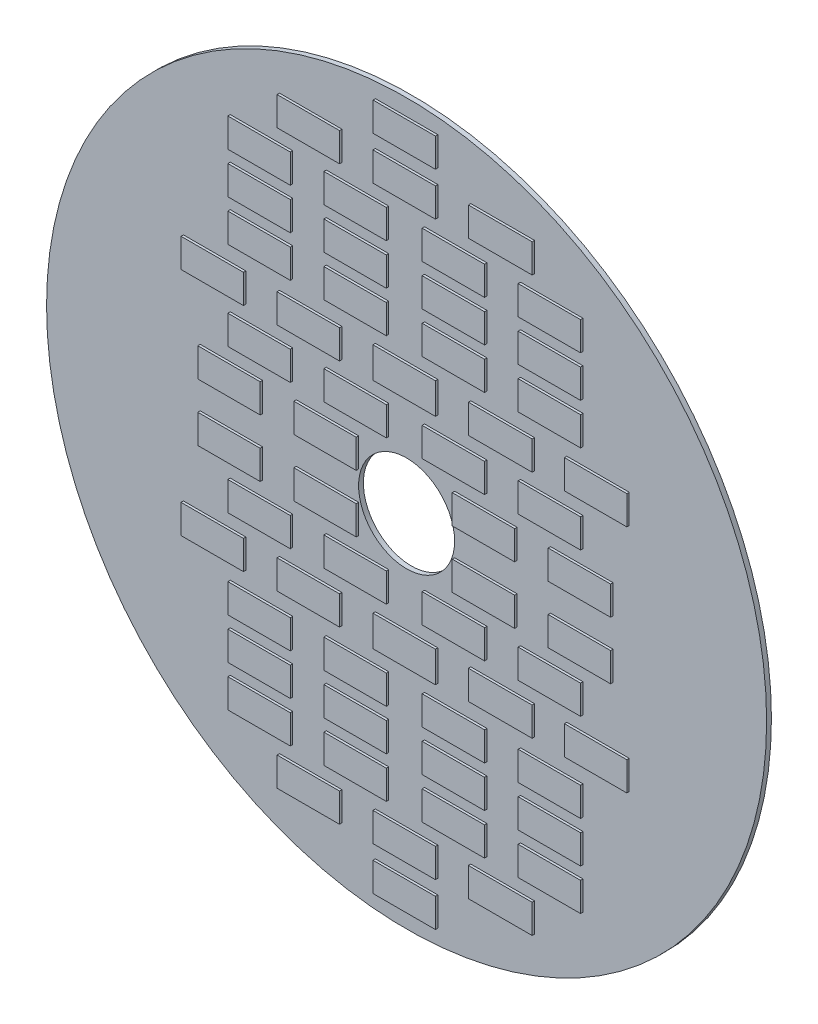
SolidWorks part; units mm, degrees
ref_plane "前视基准面" through (0, 0, 0) normal (0, 0, 1) x (1, 0, 0)
ref_plane "上视基准面" through (0, 0, 0) normal (0, 1, 0) x (1, 0, 0)
ref_plane "右视基准面" through (0, 0, 0) normal (1, 0, 0) x (0, 0, -1)
other "Configuration Table"
sketch "草图1" plane through (0, 0, 0) normal (0, 0, 1) x (1, 0, 0)
  line L5 (100, 90) -> (230, 90)
  line L6 (100, 90) -> (100, 30)
  line L8 (100, 30) -> (230, 30)
  line L12 (230, 90) -> (230, 30)
  line L14 (100, 90) -> (230, 30) construction
  line L18 (100, 30) -> (230, 90) construction
  line L24 (-1658.199, 0) -> (1658.199, 0) construction
  line L26 (0, 1113.9389) -> (0, -1113.9389) construction
  line L50 (300, 90) -> (430, 90)
  line L53 (300, 90) -> (300, 30)
  line L57 (300, 30) -> (430, 30)
  line L58 (430, 90) -> (430, 30)
  line L59 (300, 90) -> (430, 30) construction
  line L60 (300, 30) -> (430, 90) construction
  line L61 (37.3566, 180) -> (37.3566, 120)
  line L62 (237.3566, 120) -> (367.3566, 120)
  line L63 (237.3566, 180) -> (367.3566, 120) construction
  line L64 (37.3566, 120) -> (167.3566, 180) construction
  line L65 (237.3566, 180) -> (237.3566, 120)
  line L66 (367.3566, 180) -> (367.3566, 120)
  line L67 (37.3566, 180) -> (167.3566, 180)
  line L68 (37.3566, 180) -> (167.3566, 120) construction
  line L69 (237.3566, 180) -> (367.3566, 180)
  line L70 (237.3566, 120) -> (367.3566, 180) construction
  line L71 (37.3566, 120) -> (167.3566, 120)
  line L72 (167.3566, 180) -> (167.3566, 120)
  line L83 (37.3566, 364.2375) -> (37.3566, 304.2375)
  line L84 (237.3566, 304.2375) -> (367.3566, 304.2375)
  line L91 (133.7252, 270) -> (133.7252, 210)
  line L92 (333.7252, 210) -> (463.7252, 210)
  line L93 (333.7252, 270) -> (463.7252, 210) construction
  line L94 (133.7252, 210) -> (266.6142, 270) construction
  line L95 (333.7252, 270) -> (333.7252, 210)
  line L96 (463.7252, 270) -> (463.7252, 210)
  line L97 (133.7252, 270) -> (266.6142, 270)
  line L98 (133.7252, 270) -> (266.6142, 210) construction
  line L99 (333.7252, 270) -> (463.7252, 270)
  line L100 (333.7252, 210) -> (463.7252, 270) construction
  line L101 (133.7252, 210) -> (266.6142, 210)
  line L102 (266.6142, 270) -> (266.6142, 210)
  line L103 (-65, 274.2375) -> (-65, 210)
  line L104 (-65, 274.2375) -> (65, 274.2375)
  line L105 (-65, 210) -> (65, 210)
  line L106 (65, 274.2375) -> (65, 210)
  line L107 (-65, 210) -> (65, 274.2375) construction
  line L108 (-65, 274.2375) -> (65, 210) construction
  line L109 (-264.8303, 270) -> (-264.8303, 210)
  line L110 (-264.8303, 270) -> (-134.8303, 270)
  line L111 (-264.8303, 210) -> (-134.8303, 210)
  line L112 (-134.8303, 270) -> (-134.8303, 210)
  line L113 (-264.8303, 210) -> (-134.8303, 270) construction
  line L114 (-264.8303, 270) -> (-134.8303, 210) construction
  line L115 (-464.8303, 270) -> (-464.8303, 210)
  line L116 (-464.8303, 270) -> (-334.8303, 270)
  line L117 (-464.8303, 210) -> (-334.8303, 210)
  line L118 (-334.8303, 270) -> (-334.8303, 210)
  line L119 (-464.8303, 210) -> (-334.8303, 270) construction
  line L120 (-464.8303, 270) -> (-334.8303, 210) construction
  line L122 (237.3566, 364.2375) -> (237.3566, 304.2375)
  line L123 (367.3566, 364.2375) -> (367.3566, 304.2375)
  line L125 (37.3566, 364.2375) -> (167.3566, 364.2375)
  line L127 (237.3566, 364.2375) -> (367.3566, 364.2375)
  line L128 (37.3566, 304.2375) -> (167.3566, 304.2375)
  line L129 (167.3566, 364.2375) -> (167.3566, 304.2375)
  line L139 (237.3566, 364.2375) -> (367.3566, 304.2375) construction
  line L140 (37.3566, 304.2375) -> (167.3566, 364.2375) construction
  line L141 (37.3566, 364.2375) -> (167.3566, 304.2375) construction
  line L142 (237.3566, 304.2375) -> (367.3566, 364.2375) construction
  line L143 (37.3566, 450) -> (37.3566, 390)
  line L144 (237.3566, 390) -> (367.3566, 390)
  line L145 (237.3566, 450) -> (237.3566, 390)
  line L146 (367.3566, 450) -> (367.3566, 390)
  line L147 (37.3566, 450) -> (167.3566, 450)
  line L148 (237.3566, 450) -> (367.3566, 450)
  line L149 (37.3566, 390) -> (167.3566, 390)
  line L150 (167.3566, 450) -> (167.3566, 390)
  line L151 (237.3566, 450) -> (367.3566, 390) construction
  line L152 (37.3566, 390) -> (167.3566, 450) construction
  line L153 (37.3566, 450) -> (167.3566, 390) construction
  line L154 (237.3566, 390) -> (367.3566, 450) construction
  line L155 (37.3566, 535.7625) -> (37.3566, 475.7625)
  line L156 (237.3566, 475.7625) -> (367.3566, 475.7625)
  line L157 (237.3566, 535.7625) -> (237.3566, 475.7625)
  line L158 (367.3566, 535.7625) -> (367.3566, 475.7625)
  line L159 (37.3566, 535.7625) -> (167.3566, 535.7625)
  line L160 (237.3566, 535.7625) -> (367.3566, 535.7625)
  line L161 (37.3566, 475.7625) -> (167.3566, 475.7625)
  line L162 (167.3566, 535.7625) -> (167.3566, 475.7625)
  line L163 (237.3566, 535.7625) -> (367.3566, 475.7625) construction
  line L164 (37.3566, 475.7625) -> (167.3566, 535.7625) construction
  line L165 (37.3566, 535.7625) -> (167.3566, 475.7625) construction
  line L166 (237.3566, 475.7625) -> (367.3566, 535.7625) construction
  line L167 (-264.8303, 565.7625) -> (-134.8303, 625.7625) construction
  line L168 (133.7252, 565.7625) -> (266.6142, 565.7625)
  line L169 (-65, 565.7625) -> (65, 625.7625) construction
  line L170 (-65, 625.7625) -> (-65, 565.7625)
  line L171 (-264.8303, 625.7625) -> (-264.8303, 565.7625)
  line L172 (-134.8303, 625.7625) -> (-134.8303, 565.7625)
  line L173 (133.7252, 625.7625) -> (266.6142, 625.7625)
  line L174 (133.7252, 625.7625) -> (266.6142, 565.7625) construction
  line L175 (65, 625.7625) -> (65, 565.7625)
  line L176 (-264.8303, 625.7625) -> (-134.8303, 565.7625) construction
  line L177 (133.7252, 625.7625) -> (133.7252, 565.7625)
  line L178 (-65, 625.7625) -> (65, 625.7625)
  line L179 (-65, 565.7625) -> (65, 565.7625)
  line L180 (-264.8303, 565.7625) -> (-134.8303, 565.7625)
  line L181 (133.7252, 565.7625) -> (266.6142, 625.7625) construction
  line L182 (266.6142, 625.7625) -> (266.6142, 565.7625)
  line L183 (-264.8303, 625.7625) -> (-134.8303, 625.7625)
  line L184 (-65, 625.7625) -> (65, 565.7625) construction
  line L185 (-300, 90) -> (-300, 30)
  line L186 (-300, 30) -> (-430, 30)
  line L187 (-430, 90) -> (-430, 30)
  line L188 (-300, 90) -> (-430, 90)
  line L189 (-100, 30) -> (-230, 30)
  line L190 (-230, 90) -> (-230, 30)
  line L191 (-100, 90) -> (-230, 90)
  line L192 (-100, 90) -> (-100, 30)
  line L193 (-37.3566, 180) -> (-167.3566, 180)
  line L194 (-167.3566, 180) -> (-167.3566, 120)
  line L195 (-37.3566, 120) -> (-167.3566, 120)
  line L196 (-37.3566, 180) -> (-37.3566, 120)
  line L197 (-237.3566, 180) -> (-237.3566, 120)
  line L198 (-237.3566, 180) -> (-367.3566, 180)
  line L199 (-367.3566, 180) -> (-367.3566, 120)
  line L200 (-237.3566, 120) -> (-367.3566, 120)
  line L201 (-237.3566, 475.7625) -> (-367.3566, 535.7625) construction
  line L202 (-37.3566, 535.7625) -> (-167.3566, 475.7625) construction
  line L203 (-37.3566, 475.7625) -> (-167.3566, 535.7625) construction
  line L204 (-237.3566, 535.7625) -> (-367.3566, 475.7625) construction
  line L205 (-237.3566, 390) -> (-367.3566, 450) construction
  line L206 (-37.3566, 450) -> (-167.3566, 390) construction
  line L207 (-37.3566, 390) -> (-167.3566, 450) construction
  line L208 (-237.3566, 450) -> (-367.3566, 390) construction
  line L209 (-237.3566, 304.2375) -> (-367.3566, 364.2375) construction
  line L210 (-37.3566, 364.2375) -> (-167.3566, 304.2375) construction
  line L211 (-37.3566, 304.2375) -> (-167.3566, 364.2375) construction
  line L212 (-237.3566, 364.2375) -> (-367.3566, 304.2375) construction
  line L213 (-167.3566, 535.7625) -> (-167.3566, 475.7625)
  line L214 (-37.3566, 475.7625) -> (-167.3566, 475.7625)
  line L215 (-237.3566, 535.7625) -> (-367.3566, 535.7625)
  line L216 (-37.3566, 535.7625) -> (-167.3566, 535.7625)
  line L217 (-367.3566, 535.7625) -> (-367.3566, 475.7625)
  line L218 (-237.3566, 535.7625) -> (-237.3566, 475.7625)
  line L219 (-237.3566, 475.7625) -> (-367.3566, 475.7625)
  line L220 (-37.3566, 535.7625) -> (-37.3566, 475.7625)
  line L221 (-167.3566, 450) -> (-167.3566, 390)
  line L222 (-37.3566, 390) -> (-167.3566, 390)
  line L223 (-237.3566, 450) -> (-367.3566, 450)
  line L224 (-37.3566, 450) -> (-167.3566, 450)
  line L225 (-367.3566, 450) -> (-367.3566, 390)
  line L226 (-237.3566, 450) -> (-237.3566, 390)
  line L227 (-237.3566, 390) -> (-367.3566, 390)
  line L228 (-37.3566, 450) -> (-37.3566, 390)
  line L229 (-167.3566, 364.2375) -> (-167.3566, 304.2375)
  line L230 (-37.3566, 304.2375) -> (-167.3566, 304.2375)
  line L231 (-237.3566, 364.2375) -> (-367.3566, 364.2375)
  line L232 (-37.3566, 364.2375) -> (-167.3566, 364.2375)
  line L233 (-367.3566, 364.2375) -> (-367.3566, 304.2375)
  line L234 (-237.3566, 364.2375) -> (-237.3566, 304.2375)
  line L235 (-237.3566, 304.2375) -> (-367.3566, 304.2375)
  line L236 (-37.3566, 364.2375) -> (-37.3566, 304.2375)
  line L237 (-237.3566, -364.2375) -> (-367.3566, -304.2375) construction
  line L238 (-37.3566, -304.2375) -> (-167.3566, -364.2375) construction
  line L239 (-37.3566, -364.2375) -> (-167.3566, -304.2375) construction
  line L240 (-237.3566, -304.2375) -> (-367.3566, -364.2375) construction
  line L241 (-237.3566, -450) -> (-367.3566, -390) construction
  line L242 (-37.3566, -390) -> (-167.3566, -450) construction
  line L243 (-37.3566, -450) -> (-167.3566, -390) construction
  line L244 (-237.3566, -390) -> (-367.3566, -450) construction
  line L245 (-237.3566, -535.7625) -> (-367.3566, -475.7625) construction
  line L246 (-37.3566, -475.7625) -> (-167.3566, -535.7625) construction
  line L247 (-37.3566, -535.7625) -> (-167.3566, -475.7625) construction
  line L248 (-237.3566, -475.7625) -> (-367.3566, -535.7625) construction
  line L249 (-65, -625.7625) -> (65, -565.7625) construction
  line L250 (133.7252, -565.7625) -> (266.6142, -625.7625) construction
  line L251 (-264.8303, -625.7625) -> (-134.8303, -565.7625) construction
  line L252 (133.7252, -625.7625) -> (266.6142, -565.7625) construction
  line L253 (-65, -565.7625) -> (65, -625.7625) construction
  line L254 (-264.8303, -565.7625) -> (-134.8303, -625.7625) construction
  line L255 (237.3566, -475.7625) -> (367.3566, -535.7625) construction
  line L256 (37.3566, -535.7625) -> (167.3566, -475.7625) construction
  line L257 (37.3566, -475.7625) -> (167.3566, -535.7625) construction
  line L258 (237.3566, -535.7625) -> (367.3566, -475.7625) construction
  line L259 (237.3566, -390) -> (367.3566, -450) construction
  line L260 (37.3566, -450) -> (167.3566, -390) construction
  line L261 (37.3566, -390) -> (167.3566, -450) construction
  line L262 (237.3566, -450) -> (367.3566, -390) construction
  line L263 (237.3566, -304.2375) -> (367.3566, -364.2375) construction
  line L264 (37.3566, -364.2375) -> (167.3566, -304.2375) construction
  line L265 (37.3566, -304.2375) -> (167.3566, -364.2375) construction
  line L266 (237.3566, -364.2375) -> (367.3566, -304.2375) construction
  line L267 (-464.8303, -270) -> (-334.8303, -210) construction
  line L268 (-464.8303, -210) -> (-334.8303, -270) construction
  line L269 (-264.8303, -270) -> (-134.8303, -210) construction
  line L270 (-264.8303, -210) -> (-134.8303, -270) construction
  line L271 (-65, -274.2375) -> (65, -210) construction
  line L272 (-65, -210) -> (65, -274.2375) construction
  line L273 (333.7252, -210) -> (463.7252, -270) construction
  line L274 (133.7252, -270) -> (266.6142, -210) construction
  line L275 (133.7252, -210) -> (266.6142, -270) construction
  line L276 (333.7252, -270) -> (463.7252, -210) construction
  line L277 (237.3566, -120) -> (367.3566, -180) construction
  line L278 (37.3566, -180) -> (167.3566, -120) construction
  line L279 (37.3566, -120) -> (167.3566, -180) construction
  line L280 (237.3566, -180) -> (367.3566, -120) construction
  line L281 (300, -30) -> (430, -90) construction
  line L282 (300, -90) -> (430, -30) construction
  line L283 (100, -30) -> (230, -90) construction
  line L284 (100, -90) -> (230, -30) construction
  line L285 (-37.3566, -364.2375) -> (-37.3566, -304.2375)
  line L286 (-237.3566, -304.2375) -> (-367.3566, -304.2375)
  line L287 (-237.3566, -364.2375) -> (-237.3566, -304.2375)
  line L288 (-367.3566, -364.2375) -> (-367.3566, -304.2375)
  line L289 (-37.3566, -364.2375) -> (-167.3566, -364.2375)
  line L290 (-237.3566, -364.2375) -> (-367.3566, -364.2375)
  line L291 (-37.3566, -304.2375) -> (-167.3566, -304.2375)
  line L292 (-167.3566, -364.2375) -> (-167.3566, -304.2375)
  line L293 (-37.3566, -450) -> (-37.3566, -390)
  line L294 (-237.3566, -390) -> (-367.3566, -390)
  line L295 (-237.3566, -450) -> (-237.3566, -390)
  line L296 (-367.3566, -450) -> (-367.3566, -390)
  line L297 (-37.3566, -450) -> (-167.3566, -450)
  line L298 (-237.3566, -450) -> (-367.3566, -450)
  line L299 (-37.3566, -390) -> (-167.3566, -390)
  line L300 (-167.3566, -450) -> (-167.3566, -390)
  line L301 (-37.3566, -535.7625) -> (-37.3566, -475.7625)
  line L302 (-237.3566, -475.7625) -> (-367.3566, -475.7625)
  line L303 (-237.3566, -535.7625) -> (-237.3566, -475.7625)
  line L304 (-367.3566, -535.7625) -> (-367.3566, -475.7625)
  line L305 (-37.3566, -535.7625) -> (-167.3566, -535.7625)
  line L306 (-237.3566, -535.7625) -> (-367.3566, -535.7625)
  line L307 (-37.3566, -475.7625) -> (-167.3566, -475.7625)
  line L308 (-167.3566, -535.7625) -> (-167.3566, -475.7625)
  line L309 (-237.3566, -120) -> (-367.3566, -120)
  line L310 (-367.3566, -180) -> (-367.3566, -120)
  line L311 (-237.3566, -180) -> (-367.3566, -180)
  line L312 (-237.3566, -180) -> (-237.3566, -120)
  line L313 (-37.3566, -180) -> (-37.3566, -120)
  line L314 (-37.3566, -120) -> (-167.3566, -120)
  line L315 (-167.3566, -180) -> (-167.3566, -120)
  line L316 (-37.3566, -180) -> (-167.3566, -180)
  line L317 (-100, -90) -> (-100, -30)
  line L318 (-100, -90) -> (-230, -90)
  line L319 (-230, -90) -> (-230, -30)
  line L320 (-100, -30) -> (-230, -30)
  line L321 (-300, -90) -> (-430, -90)
  line L322 (-430, -90) -> (-430, -30)
  line L323 (-300, -30) -> (-430, -30)
  line L324 (-300, -90) -> (-300, -30)
  line L325 (-264.8303, -625.7625) -> (-134.8303, -625.7625)
  line L326 (266.6142, -625.7625) -> (266.6142, -565.7625)
  line L327 (-264.8303, -565.7625) -> (-134.8303, -565.7625)
  line L328 (-65, -565.7625) -> (65, -565.7625)
  line L329 (-65, -625.7625) -> (65, -625.7625)
  line L330 (133.7252, -625.7625) -> (133.7252, -565.7625)
  line L331 (65, -625.7625) -> (65, -565.7625)
  line L332 (133.7252, -625.7625) -> (266.6142, -625.7625)
  line L333 (-134.8303, -625.7625) -> (-134.8303, -565.7625)
  line L334 (-264.8303, -625.7625) -> (-264.8303, -565.7625)
  line L335 (-65, -625.7625) -> (-65, -565.7625)
  line L336 (133.7252, -565.7625) -> (266.6142, -565.7625)
  line L337 (167.3566, -535.7625) -> (167.3566, -475.7625)
  line L338 (37.3566, -475.7625) -> (167.3566, -475.7625)
  line L339 (237.3566, -535.7625) -> (367.3566, -535.7625)
  line L340 (37.3566, -535.7625) -> (167.3566, -535.7625)
  line L341 (367.3566, -535.7625) -> (367.3566, -475.7625)
  line L342 (237.3566, -535.7625) -> (237.3566, -475.7625)
  line L343 (237.3566, -475.7625) -> (367.3566, -475.7625)
  line L344 (37.3566, -535.7625) -> (37.3566, -475.7625)
  line L345 (167.3566, -450) -> (167.3566, -390)
  line L346 (37.3566, -390) -> (167.3566, -390)
  line L347 (237.3566, -450) -> (367.3566, -450)
  line L348 (37.3566, -450) -> (167.3566, -450)
  line L349 (367.3566, -450) -> (367.3566, -390)
  line L350 (237.3566, -450) -> (237.3566, -390)
  line L351 (237.3566, -390) -> (367.3566, -390)
  line L352 (37.3566, -450) -> (37.3566, -390)
  line L353 (167.3566, -364.2375) -> (167.3566, -304.2375)
  line L354 (37.3566, -304.2375) -> (167.3566, -304.2375)
  line L355 (237.3566, -364.2375) -> (367.3566, -364.2375)
  line L356 (37.3566, -364.2375) -> (167.3566, -364.2375)
  line L357 (367.3566, -364.2375) -> (367.3566, -304.2375)
  line L358 (237.3566, -364.2375) -> (237.3566, -304.2375)
  line L359 (-334.8303, -270) -> (-334.8303, -210)
  line L360 (-464.8303, -210) -> (-334.8303, -210)
  line L361 (-464.8303, -270) -> (-334.8303, -270)
  line L362 (-464.8303, -270) -> (-464.8303, -210)
  line L363 (-134.8303, -270) -> (-134.8303, -210)
  line L364 (-264.8303, -210) -> (-134.8303, -210)
  line L365 (-264.8303, -270) -> (-134.8303, -270)
  line L366 (-264.8303, -270) -> (-264.8303, -210)
  line L367 (65, -274.2375) -> (65, -210)
  line L368 (-65, -210) -> (65, -210)
  line L369 (-65, -274.2375) -> (65, -274.2375)
  line L370 (-65, -274.2375) -> (-65, -210)
  line L371 (266.6142, -270) -> (266.6142, -210)
  line L372 (133.7252, -210) -> (266.6142, -210)
  line L373 (333.7252, -270) -> (463.7252, -270)
  line L374 (133.7252, -270) -> (266.6142, -270)
  line L375 (463.7252, -270) -> (463.7252, -210)
  line L376 (333.7252, -270) -> (333.7252, -210)
  line L377 (333.7252, -210) -> (463.7252, -210)
  line L378 (133.7252, -270) -> (133.7252, -210)
  line L379 (237.3566, -304.2375) -> (367.3566, -304.2375)
  line L380 (37.3566, -364.2375) -> (37.3566, -304.2375)
  line L381 (167.3566, -180) -> (167.3566, -120)
  line L382 (37.3566, -120) -> (167.3566, -120)
  line L383 (237.3566, -180) -> (367.3566, -180)
  line L384 (37.3566, -180) -> (167.3566, -180)
  line L385 (367.3566, -180) -> (367.3566, -120)
  line L386 (237.3566, -180) -> (237.3566, -120)
  line L387 (237.3566, -120) -> (367.3566, -120)
  line L388 (37.3566, -180) -> (37.3566, -120)
  line L389 (430, -90) -> (430, -30)
  line L390 (300, -30) -> (430, -30)
  line L391 (300, -90) -> (300, -30)
  line L392 (300, -90) -> (430, -90)
  line L393 (230, -90) -> (230, -30)
  line L394 (100, -30) -> (230, -30)
  line L395 (100, -90) -> (100, -30)
  line L396 (100, -90) -> (230, -90)
  line L397 (-65, 715.7625) -> (65, 715.7625)
  line L398 (-65, 715.7625) -> (65, 655.7625) construction
  line L399 (65, 715.7625) -> (65, 655.7625)
  line L400 (-65, 655.7625) -> (65, 715.7625) construction
  line L401 (-65, 715.7625) -> (-65, 655.7625)
  line L402 (-65, 655.7625) -> (65, 655.7625)
  line L403 (-65, -655.7625) -> (65, -715.7625) construction
  line L404 (-65, -715.7625) -> (65, -655.7625) construction
  line L405 (-65, -655.7625) -> (65, -655.7625)
  line L406 (-65, -715.7625) -> (-65, -655.7625)
  line L407 (65, -715.7625) -> (65, -655.7625)
  line L408 (-65, -715.7625) -> (65, -715.7625)
  circle A0 centre (0, 0) radius 750 construction
  point P0 (165, 60)
  point P5 (102.3566, 150)
  point P7 (365, 60)
  point P16 (302.3566, 192.8005)
  point P24 (200.1697, 595.7625)
  point P26 (200.1697, 240)
  point P29 (102.3566, 334.2375)
  point P39 (102.3566, 420)
  point P47 (0, 274.2375)
  point P70 (102.3566, 505.7625)
  point P80 (302.3566, 462.8005)
  point P81 (302.3566, 377.038)
  point P132 (-102.3566, 505.7625)
  point P133 (-102.3566, 420)
  point P134 (-102.3566, 334.2375)
  point P247 (-102.3566, -334.2375)
  point P248 (-102.3566, -420)
  point P249 (-102.3566, -505.7625)
  point P250 (102.3566, -505.7625)
  point P251 (102.3566, -420)
  point P252 (102.3566, -334.2375)
  point P253 (200.1697, -240)
  point P254 (200.1697, -595.7625)
  point P255 (302.3566, -192.8005)
  point P256 (365, -60)
  point P257 (102.3566, -150)
  point P258 (165, -60)
  dimension "D3" = 100
  dimension "D1" = 2
  dimension "D2" = 30
  dimension "D4" = 30
  dimension "D5" = 60
  dimension "D6" = 130
  dimension "D7" = 70
  dimension "D8" = 70
  dimension "D9" = 2
  dimension "D10" = 3
  dimension "D11" = 130
  dimension "D12" = 60
  dimension "D13" = 30
  dimension "D14" = 60
  dimension "D15" = 30
sketch "草图2" plane through (0, 0, 0) normal (0, 0, 1) x (1, 0, 0)
  circle A0 centre (0, 0) radius 750
  circle A1 centre (0, 0) radius 100
  dimension "D1" = 1500
  dimension "D2" = 200
extrude "凸台-拉伸1" add sketch "草图2" along normal blind 10
extrude "凸台-拉伸2" add sketch "草图1" along normal blind 15
